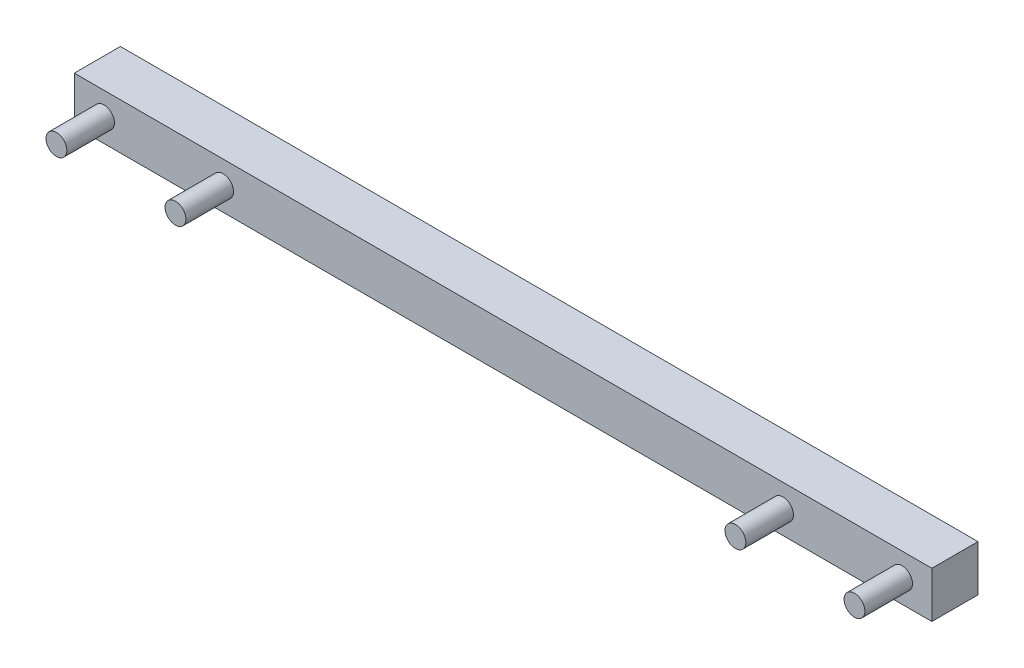
SolidWorks part; units mm, degrees
ref_plane "前视基准面" through (0, 0, 0) normal (0, 0, 1) x (1, 0, 0)
ref_plane "上视基准面" through (0, 0, 0) normal (0, 1, 0) x (1, 0, 0)
ref_plane "右视基准面" through (0, 0, 0) normal (1, 0, 0) x (0, 0, -1)
sketch "草图2" plane through (0, 0, 0) normal (0, 0, 1) x (1, 0, 0)
  circle A0 centre (-164, 0) radius 3.5
  circle A1 centre (24.1, 0) radius 3.5
  circle A2 centre (-204, 0) radius 3.5
  circle A3 centre (64.1, 0) radius 3.5
  dimension "D1" = 7
  dimension "D2" = 188.1
  dimension "D4" = 40
  dimension "D5" = 40
extrude "凸台-拉伸1" add sketch "草图2" along normal blind 16
sketch "草图3" plane through (0, 0, 0) normal (0, 0, -1) x (-1, 0, 0)
  line L1 (214, 7.75) -> (-74.1, 7.75)
  line L2 (214, 7.75) -> (214, -7.75)
  line L3 (214, -7.75) -> (-74.1, -7.75)
  line L4 (-74.1, 7.75) -> (-74.1, -7.75)
  circle A0 centre (-64.1, 0) radius 3.5 construction
  circle A1 centre (204, 0) radius 3.5 construction
  dimension "D2" = 10
  dimension "D3" = 10
  dimension "D1" = 15.5
extrude "凸台-拉伸2" add sketch "草图3" along normal blind 15.5
